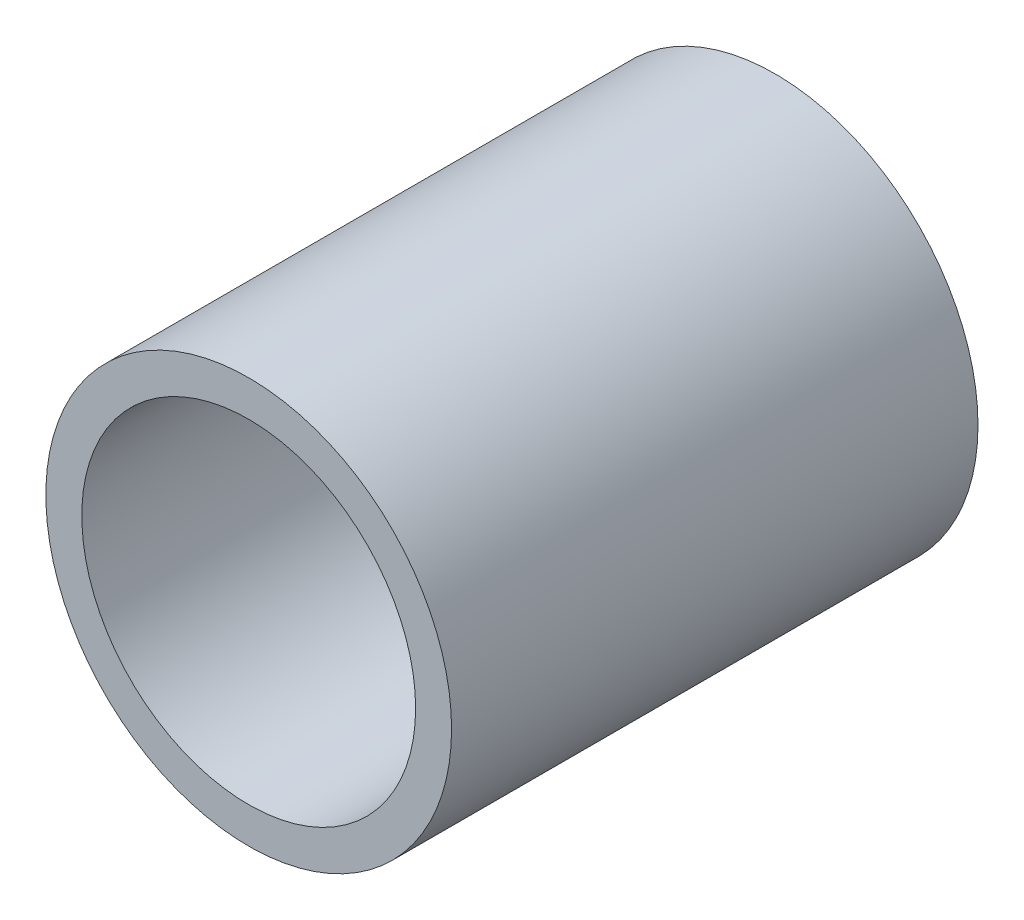
SolidWorks part; units mm, degrees
ref_plane "Front Plane" through (0, 0, 0) normal (0, 0, 1) x (1, 0, 0)
ref_plane "Top Plane" through (0, 0, 0) normal (0, 1, 0) x (1, 0, 0)
ref_plane "Right Plane" through (0, 0, 0) normal (1, 0, 0) x (0, 0, -1)
sketch "Sketch1" plane through (0, 0, 0) normal (0, 0, 1) x (1, 0, 0)
  circle A0 centre (0, 0) radius 20.066
  circle A1 centre (0, 0) radius 16.51
  dimension "D1" = 40.132
  dimension "D2" = 33.02
extrude "Boss-Extrude1" add sketch "Sketch1" along normal blind 52.07
ref_plane "Pipe (1in) #1" through (0, 0, 33.02) normal (0, 0, 1) x (1, 0, 0)
ref_plane "Pipe (1in) #2" through (0, 0, 19.05) normal (0, 0, 1) x (1, 0, 0)
